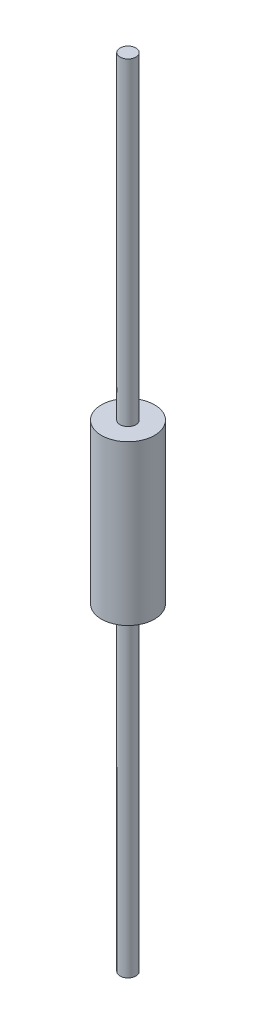
SolidWorks part; units mm, degrees
ref_plane "Front Plane" through (0, 0, 0) normal (0, 0, 1) x (1, 0, 0)
ref_plane "Top Plane" through (0, 0, 0) normal (0, 1, 0) x (1, 0, 0)
ref_plane "Right Plane" through (0, 0, 0) normal (1, 0, 0) x (0, 0, -1)
sketch "Sketch1" plane through (0, 0, 0) normal (0, 1, 0) x (1, 0, 0)
  circle A0 centre (0, 0) radius 0.5
  dimension "D1" = 1
extrude "Boss-Extrude1" add sketch "Sketch1" along normal blind 3
sketch "Sketch2" plane through (0, 3, 0) normal (0, 1, 0) x (1, 0, 0)
  circle A0 centre (0, 0) radius 0.15
  dimension "D1" = 0.3
extrude "Boss-Extrude2" add sketch "Sketch2" along normal blind 6
sketch "Sketch3" plane through (0, 0, 0) normal (0, -1, 0) x (1, 0, 0)
  circle A0 centre (0, 0) radius 0.15
  dimension "D1" = 0.3
extrude "Boss-Extrude3" add sketch "Sketch3" along normal blind 6
sketch "Sketch4" plane through (0, 9, 0) normal (0, 1, 0) x (1, 0, 0)
  line L0 (0, 0) -> (0, -0.15) construction
  circle A0 centre (0, 0) radius 0.15 construction
ref_plane "Plane1" through (0, 0, -0.15) normal (0, 0, -1) x (-1, 0, 0)
